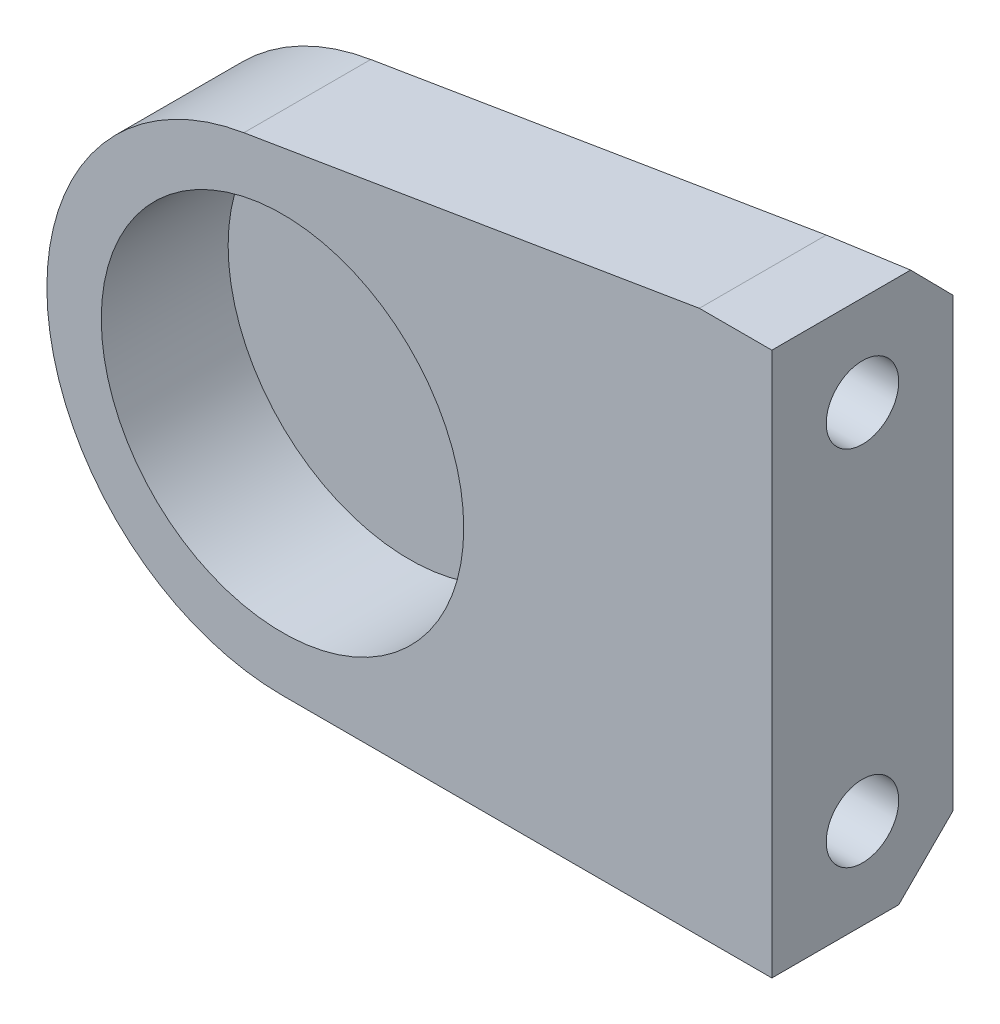
SolidWorks part; units mm, degrees
ref_plane "Front Plane" through (0, 0, 0) normal (0, 0, 1) x (1, 0, 0)
ref_plane "Top Plane" through (0, 0, 0) normal (0, 1, 0) x (1, 0, 0)
ref_plane "Right Plane" through (0, 0, 0) normal (1, 0, 0) x (0, 0, -1)
sketch "Sketch1" plane through (0, 0, 0) normal (0, 0, 1) x (1, 0, 0)
  line L0 (0, -6.5) -> (13.5, -6.5)
  line L1 (13.5, -6.5) -> (13.5, 8.5)
  line L2 (13.5, 8.5) -> (11.5, 8.5)
  line L3 (11.5, 8.5) -> (-1.0655, 6.4121)
  arc A1 (0, -6.5) -> (-1.0655, 6.4121) centre (0, 0) cw
  dimension "D3" = 6.5
  dimension "D2" = 6.5
  dimension "D4" = 13.5
  dimension "D5" = 15
  dimension "D6" = 2
extrude "Boss-Extrude1" add sketch "Sketch1" along normal blind 5
sketch "Sketch2" plane through (0, 0, 5) normal (0, 0, 1) x (1, 0, 0)
  circle A0 centre (0, 0) radius 5
  dimension "D1" = 10
extrude "Cut-Extrude1" cut sketch "Sketch2" against normal blind 3.5
sketch "Sketch3" plane through (13.5, 0, 0) normal (1, 0, 0) x (0, 0, -1)
  line L0 (-2.5, 8.5) -> (-2.5, -6.5) construction
  line L2 (-5, -6.5) -> (0, -6.5) construction
  line L4 (-5, 8.5) -> (0, 8.5) construction
  line L5 (-5, -6.5) -> (0, -6.5) construction
  line L6 (-5, 1) -> (0, 1) construction
  line L7 (-5, -6.5) -> (-5, 8.5) construction
  line L8 (0, -6.5) -> (0, 8.5) construction
  circle A0 centre (-2.5, 6) radius 1
  circle A1 centre (-2.5, -4) radius 1
  dimension "D1" = 2
  dimension "D2" = 10
extrude "Cut-Extrude2" cut sketch "Sketch3" against normal blind 2
chamfer "Chamfer3" distance 1.5 angle 45 3 edges at (5.2173, 7.456, 0) (-6.478, -0.5345, 0) (6.75, -6.5, 0)
